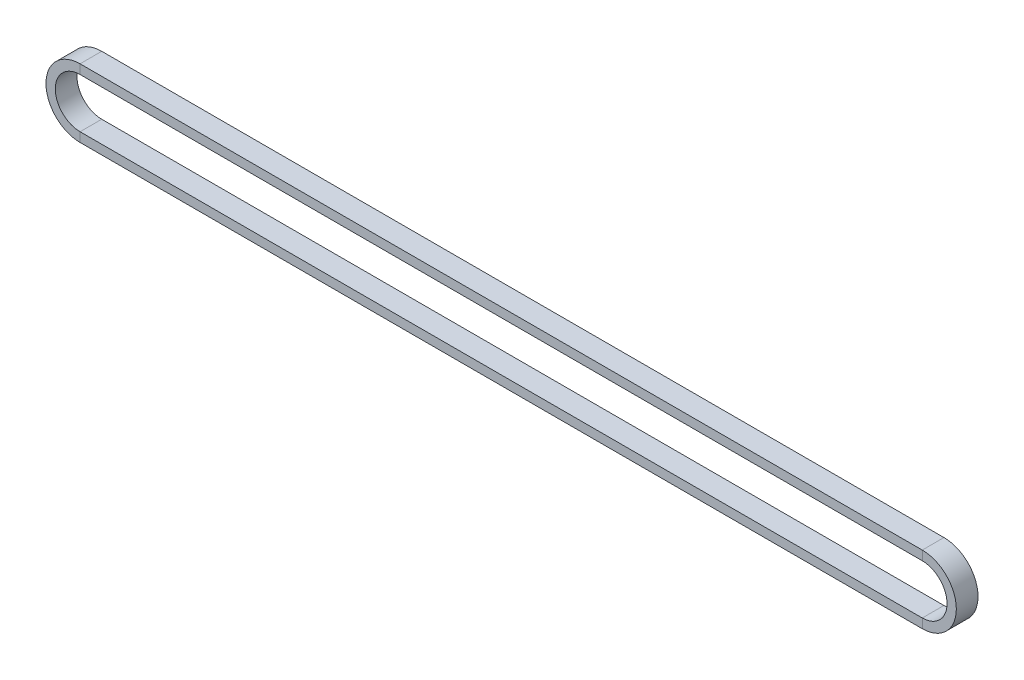
SolidWorks part; units mm, degrees
material "EPDM 60 Durometer"
ref_plane "Ebene vorne" through (0, 0, 0) normal (0, 0, 1) x (1, 0, 0)
ref_plane "Ebene oben" through (0, 0, 0) normal (0, 1, 0) x (1, 0, 0)
ref_plane "Ebene rechts" through (0, 0, 0) normal (1, 0, 0) x (0, 0, -1)
sketch "Skizze2" plane through (0, 0, 0) normal (0, 0, 1) x (1, 0, 0)
  line L0 (0, 0) -> (1, 0) construction
  line L1 (0, 0) -> (0, 1) construction
  line L2 (0, 40) -> (1360, 40)
  line L3 (1360, -40) -> (0, -40)
  arc A0 (0, -40) -> (0, 40) centre (0, 0) cw
  arc A1 (1360, 40) -> (1360, -40) centre (1360, 0) cw
sketch3d "3D-Skizze1"
  line L0 (0, 40, 0) -> (1360, 40, 0) construction
  line L2 (1360, 55, -17.5) -> (1360, 55, 17.5)
  line L3 (1360, 55, -17.5) -> (1360, 40, -17.5)
  line L4 (1360, 40, -17.5) -> (1360, 40, 17.5)
  line L5 (1360, 55, 17.5) -> (1360, 40, 17.5)
  point P7 (1360, 40, 0)
  dimension "D1" = 35
  dimension "D2" = 15
sweep "Austragung1" add profiles "3D-Skizze1" path "Skizze2"
